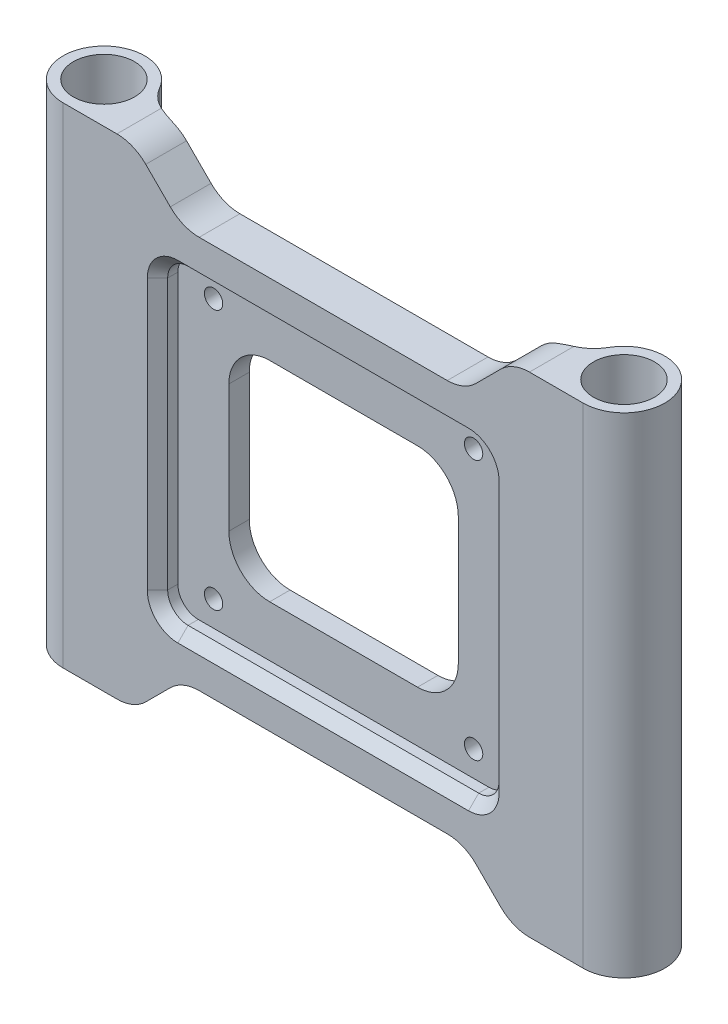
SolidWorks part; units mm, degrees
material "ABS"
ref_plane "Front Plane" through (0, 0, 0) normal (0, 0, 1) x (1, 0, 0)
ref_plane "Top Plane" through (0, 0, 0) normal (0, 1, 0) x (1, 0, 0)
ref_plane "Right Plane" through (0, 0, 0) normal (1, 0, 0) x (0, 0, -1)
sketch "Sketch1" plane through (0, 0, 0) normal (0, 1, 0) x (1, 0, 0)
  line L0 (-25.5, 4) -> (25.5, 4)
  line L1 (0, 0) -> (0, 4) construction
  line L2 (-25.5, -4) -> (25.5, -4)
  circle A1 centre (-25.5, 0) radius 4
  circle A2 centre (25.5, 0) radius 4
  point P7 (0, 0)
  point P9 (0, -4.2639)
  point P10 (0, 0)
  point P14 (0, -4)
  dimension "D1" = 8
  dimension "D2" = 25.5
extrude "Boss-Extrude1" add sketch "Sketch1" along normal mid plane 48
hole_wizard "Ø6.0mm Dowel Hole1" positions "Sketch2" profile "Sketch3" hole size "Ø6.0" standard "ANSI Metric" end condition through all
sketch "Sketch2" plane through (0, -24, 0) normal (0, -1, 0) x (-1, 0, 0)
  point P0 (25.5, 0)
  point P3 (-25.5, 0)
sketch "Sketch3" plane through (-25.5, -24, 0) normal (1, 0, 0) x (0, 0, -1)
  line L0 (0, 0) -> (0, 48)
  line L1 (0, 48) -> (3, 48)
  line L2 (3, 48) -> (3, 0)
  line L5 (3, 0) -> (0, 0)
  line L11 (0, -6.35) -> (0, 107.95) construction
  dimension "Thru Hole Dia." = 6
  dimension "Thru Hole Depth" = 48
sketch "Sketch4" plane through (0, 0, 4) normal (0, 0, -1) x (-1, 0, 0)
  line L2 (-16.25, -15.25) -> (16.25, -15.25)
  line L3 (-16.25, -15.25) -> (-16.25, 15.25)
  line L4 (-16.25, 15.25) -> (16.25, 15.25)
  line L5 (16.25, -15.25) -> (16.25, 15.25)
  line L6 (-16.25, -15.25) -> (16.25, 15.25) construction
  line L7 (-16.25, 15.25) -> (16.25, -15.25) construction
  point P0 (0, 0)
  dimension "D1" = 32.5
  dimension "D2" = 30.5
extrude "Cut-Extrude1" cut sketch "Sketch4" along normal blind 2 contours L3 L2 L5 L4
fillet "Fillet1" radius 2 4 edges at (16.25, -15.25, 3) (-16.25, 15.25, 3) (16.25, 15.25, 3) (-16.25, -15.25, 3)
sketch "Sketch5" plane through (0, -24, 0) normal (0, -1, 0) x (1, 0, 0)
  line L0 (14.25, 2) -> (-14.25, 2) construction
  line L1 (14.25, 2) -> (-14.25, 2)
  line L2 (-21.5, 0) -> (21.5, 0)
  line L3 (-25.5, -4) -> (25.5, -4)
  circle A0 centre (-25.5, 0) radius 4
  circle A1 centre (25.5, 0) radius 4
  line M6 (-25.5, -4) -> (25.5, -4)
extrude "Cut-Extrude2" cut sketch "Sketch5" against normal through all contours A1 L2 A0 M6
fillet "Fillet2" radius 4 2 edges at (21.5, 0, 0) (-21.5, 0, 0)
sketch "Sketch6" plane through (0, 0, 4) normal (0, 0, 1) x (1, 0, 0)
  line L0 (11.25, 10.25) -> (-11.25, 10.25)
  line L1 (-11.25, 10.25) -> (-11.25, -10.25)
  line L2 (-11.25, -10.25) -> (11.25, -10.25)
  line L3 (11.25, -10.25) -> (11.25, 10.25)
  line L4 (-14.25, -15.25) -> (14.25, -15.25)
  line L5 (16.25, -13.25) -> (16.25, 13.25)
  line L6 (14.25, 15.25) -> (-14.25, 15.25)
  line L7 (-16.25, 13.25) -> (-16.25, -13.25)
  line L8 (-14.25, -15.25) -> (14.25, -15.25)
  line L9 (16.25, -13.25) -> (16.25, 13.25)
  line L10 (14.25, 15.25) -> (-14.25, 15.25)
  line L11 (-16.25, 13.25) -> (-16.25, -13.25)
  arc A0 (-11.25, 10.25) -> (-11.25, 10.25) centre (-11.25, 10.25) ccw
  arc A1 (-11.25, -10.25) -> (-11.25, -10.25) centre (-11.25, -10.25) ccw
  arc A2 (11.25, -10.25) -> (11.25, -10.25) centre (11.25, -10.25) ccw
  arc A3 (11.25, 10.25) -> (11.25, 10.25) centre (11.25, 10.25) ccw
  arc A4 (14.25, -15.25) -> (16.25, -13.25) centre (14.25, -13.25) ccw
  arc A5 (16.25, 13.25) -> (14.25, 15.25) centre (14.25, 13.25) ccw
  arc A6 (-14.25, 15.25) -> (-16.25, 13.25) centre (-14.25, 13.25) ccw
  arc A7 (-16.25, -13.25) -> (-14.25, -15.25) centre (-14.25, -13.25) ccw
  arc A8 (14.25, -15.25) -> (16.25, -13.25) centre (14.25, -13.25) ccw
  arc A9 (16.25, 13.25) -> (14.25, 15.25) centre (14.25, 13.25) ccw
  arc A10 (-14.25, 15.25) -> (-16.25, 13.25) centre (-14.25, 13.25) ccw
  arc A11 (-16.25, -13.25) -> (-14.25, -15.25) centre (-14.25, -13.25) ccw
  dimension "D1" = 0
  dimension "D2" = 5
extrude "Cut-Extrude5" cut sketch "Sketch6" against normal through all contours L2 L3 L0 L1
fillet "Fillet3" radius 4 4 edges at (-11.25, -10.25, 1) (11.25, 10.25, 1) (11.25, -10.25, 1) (-11.25, 10.25, 1)
sketch "Sketch7" plane through (0, 0, 4) normal (0, 0, 1) x (1, 0, 0)
  line L0 (-18.5718, 24) -> (-13.8218, 19.25)
  line L1 (-25.5, 24) -> (25.5, 24) construction
  line L2 (-13.8218, 19.25) -> (13.8218, 19.25)
  line L3 (0, -19.25) -> (0, 19.25) construction
  line L4 (14.25, 15.25) -> (-14.25, 15.25) construction
  line L5 (18.5718, 24) -> (13.8218, 19.25)
  line L6 (0, 0) -> (15.7972, 0) construction
  line L7 (18.5718, -24) -> (13.8218, -19.25)
  line L8 (-13.8218, -19.25) -> (13.8218, -19.25)
  line L9 (-18.5718, -24) -> (-13.8218, -19.25)
  line M13 (-25.5, -24) -> (25.5, -24)
  line M15 (25.5, 24) -> (-25.5, 24)
  dimension "D1" = 4
  dimension "D2" = 45
extrude "Cut-Extrude6" cut sketch "Sketch7" against normal through all contours L5 L0 L2 M15 | L9 L7 L8 M13
fillet "Fillet4" radius 4 8 edges at (18.5718, -24, 2) (13.8218, -19.25, 2) (18.5718, 24, 2) (13.8218, 19.25, 2) (-13.8218, 19.25, 2) (-18.5718, 24, 2) (-13.8218, -19.25, 2) (-18.5718, -24, 2)
hole_wizard "M1.6 Clearance Hole1" positions "Sketch8" profile "Sketch9" hole size "M1.6" standard "ANSI Metric" end condition through all
sketch "Sketch8" plane through (0, 0, 0) normal (0, 0, -1) x (-1, 0, 0)
  point P0 (12.75, 12.75)
  point P3 (-12.75, 12.75)
  point P6 (-12.75, -12.75)
  point P9 (12.75, -12.75)
sketch "Sketch9" plane through (-12.75, 12.75, 0) normal (1, 0, 0) x (0, 1, 0)
  line L0 (0, 0) -> (0, 4)
  line L1 (0, 4) -> (0.9, 4)
  line L2 (0.9, 4) -> (0.9, 0)
  line L5 (0.9, 0) -> (0, 0)
  line L11 (0, -6.35) -> (0, 107.95) construction
  dimension "Thru Hole Dia." = 1.8
  dimension "Thru Hole Depth" = 4
chamfer "Chamfer1" distance 1 angle 45 8 edges at (-16.25, 0, 4) (-15.6642, -14.6642, 4) (-15.6642, 14.6642, 4) (0, -15.25, 4) (0, 15.25, 4) (15.6642, -14.6642, 4) (15.6642, 14.6642, 4) (16.25, 0, 4)
